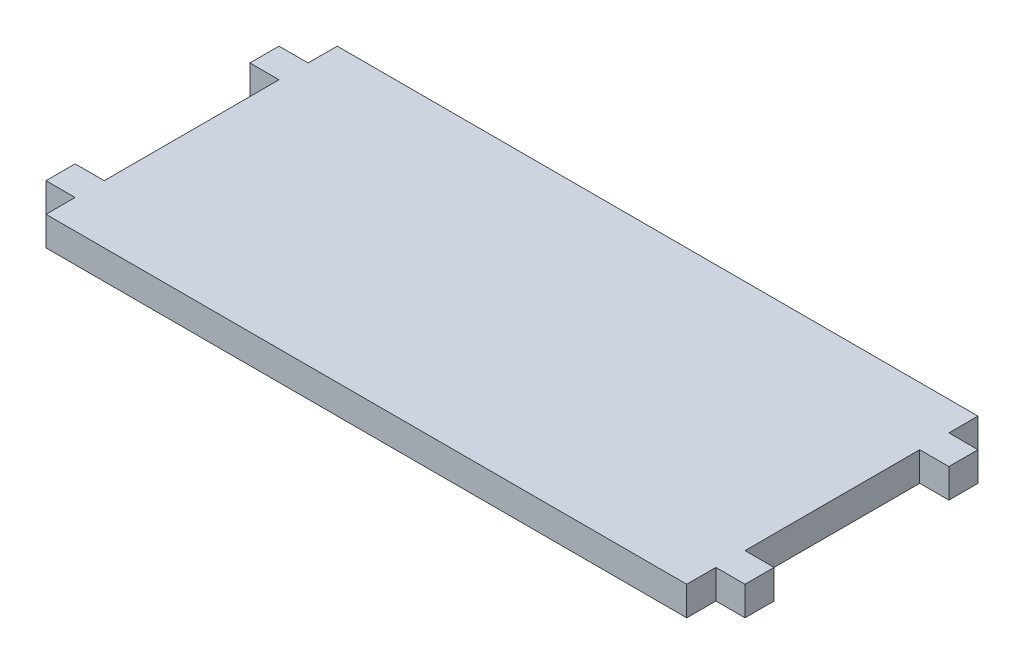
SolidWorks part; units mm, degrees
ref_plane "Front Plane" through (0, 0, 0) normal (0, 0, 1) x (1, 0, 0)
ref_plane "Top Plane" through (0, 0, 0) normal (0, 1, 0) x (1, 0, 0)
ref_plane "Right Plane" through (0, 0, 0) normal (1, 0, 0) x (0, 0, -1)
sketch "Sketch2" plane through (0, 0, 0) normal (0, 1, 0) x (1, 0, 0)
  line L1 (-91.9421, 43.5247) -> (18.0579, 43.5247)
  line L2 (-91.9421, 43.5247) -> (-91.9421, -6.4753)
  line L3 (-91.9421, -6.4753) -> (18.0579, -6.4753)
  line L4 (18.0579, 43.5247) -> (18.0579, -6.4753)
  line L5 (-91.9421, 43.5247) -> (18.0579, -6.4753) construction
  line L6 (-91.9421, -6.4753) -> (18.0579, 43.5247) construction
  point P0 (-36.9421, 18.5247)
  dimension "D1" = 110
  dimension "D2" = 50
extrude "Boss-Extrude1" add sketch "Sketch2" along normal blind 5
sketch "Sketch3" plane through (-91.9421, 0, 0) normal (-1, 0, 0) x (0, 0, 1)
  line L0 (-43.5247, 5) -> (-43.5247, 0) construction
  line L1 (-38.5247, 0) -> (-33.5247, 0)
  line L2 (-38.5247, 0) -> (-38.5247, 5)
  line L3 (-38.5247, 5) -> (-33.5247, 5)
  line L4 (-33.5247, 0) -> (-33.5247, 5)
  line L5 (-38.5247, 0) -> (-33.5247, 5) construction
  line L6 (-38.5247, 5) -> (-33.5247, 0) construction
  line L7 (1.4753, 0) -> (-3.5247, 0)
  line L8 (1.4753, 0) -> (1.4753, 5)
  line L9 (1.4753, 5) -> (-3.5247, 5)
  line L10 (-3.5247, 0) -> (-3.5247, 5)
  line L11 (1.4753, 0) -> (-3.5247, 5) construction
  line L12 (1.4753, 5) -> (-3.5247, 0) construction
  line L17 (-43.5247, 5) -> (6.4753, 5) construction
  line L18 (6.4753, 5) -> (6.4753, 0) construction
  line L19 (-43.5247, 0) -> (6.4753, 0) construction
  point P0 (-36.0247, 2.5)
  point P5 (-1.0247, 2.5)
  point P10 (-38.9463, -10.6851)
  point P13 (-36.0247, 5)
  dimension "D1" = 5
  dimension "D2" = 5
  dimension "D3" = 5
  dimension "D4" = 0
  dimension "D5" = 5
  dimension "D6" = 5
  dimension "D7" = 5
extrude "Boss-Extrude2" add sketch "Sketch3" along normal blind 5
sketch "Sketch4" plane through (18.0579, 0, 0) normal (1, 0, 0) x (0, 0, -1)
  line L0 (-6.4753, 5) -> (43.5247, 5) construction
  line L1 (38.5247, 5) -> (33.5247, 5)
  line L2 (38.5247, 5) -> (38.5247, 0)
  line L3 (38.5247, 0) -> (33.5247, 0)
  line L4 (33.5247, 5) -> (33.5247, 0)
  line L5 (-6.4753, 0) -> (43.5247, 0) construction
  line L6 (43.5247, 5) -> (43.5247, 0) construction
  line L7 (3.5247, 5) -> (-1.4753, 5)
  line L8 (3.5247, 5) -> (3.5247, 0)
  line L9 (3.5247, 0) -> (-1.4753, 0)
  line L10 (-1.4753, 5) -> (-1.4753, 0)
  line L11 (-6.4753, 5) -> (-6.4753, 0) construction
  dimension "D1" = 5
  dimension "D2" = 5
  dimension "D3" = 5
  dimension "D4" = 5
extrude "Boss-Extrude3" add sketch "Sketch4" along normal blind 5
